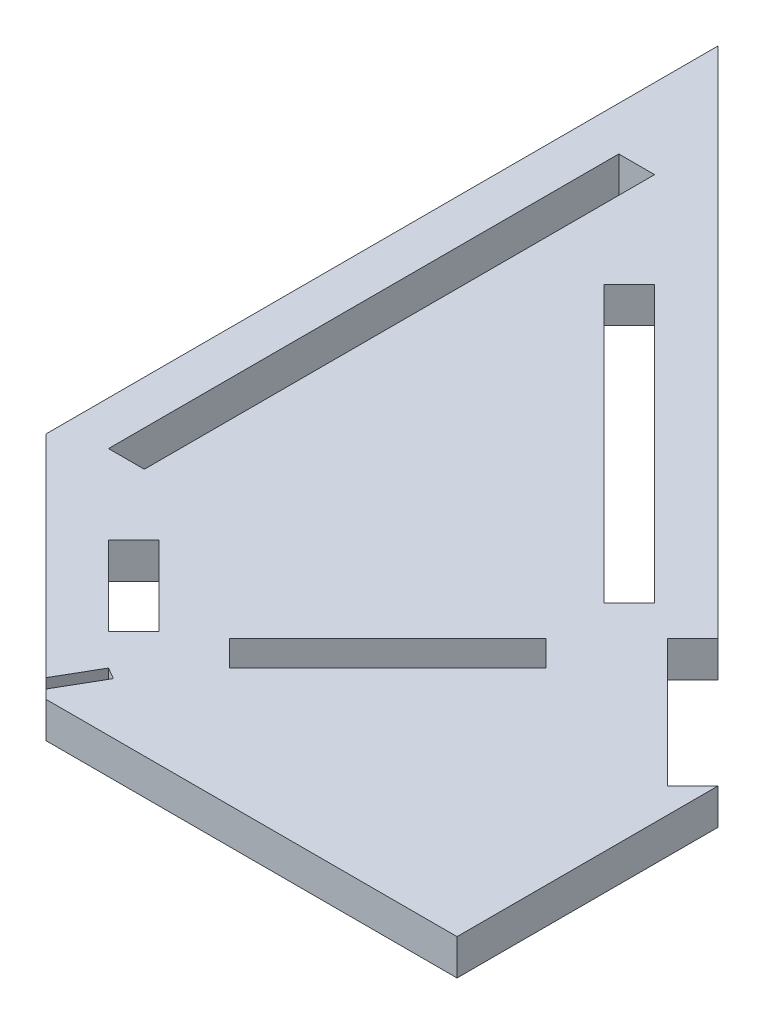
SolidWorks part; units mm, degrees
ref_plane "Front Plane" through (0, 0, 0) normal (0, 0, 1) x (1, 0, 0)
ref_plane "Top Plane" through (0, 0, 0) normal (0, 1, 0) x (1, 0, 0)
ref_plane "Right Plane" through (0, 0, 0) normal (1, 0, 0) x (0, 0, -1)
sketch "Sketch1" plane through (0, 0, 0) normal (0, 1, 0) x (1, 0, 0)
  line L0 (0, 0) -> (0, 58.25)
  line L1 (0, 58.25) -> (-143.0789, 201.3289)
  line L2 (-143.0789, 201.3289) -> (-143.0789, 51.3289)
  line L3 (-143.0789, 51.3289) -> (-95.9462, 4.1962)
  line L4 (-91.75, 0) -> (0, 0)
  line L5 (-93.75, 2) -> (-91.75, 0)
  line L6 (-82.9941, 32.1952) -> (-77.3372, 26.5383) construction
  line L7 (-47.6387, 67.5505) -> (-82.9941, 32.1952) construction
  line L8 (-47.6387, 67.5505) -> (-41.9819, 61.8937) construction
  line L9 (-298.2484, -352.2016) -> (-88.2484, 11.5291)
  line L10 (-88.2484, 11.5291) -> (-90.8465, 13.0291)
  line L11 (-90.8465, 13.0291) -> (-300.8465, -350.7016)
  line L12 (-300.8465, -350.7016) -> (-298.2484, -352.2016)
  line L13 (-93.75, 2) -> (-88.2484, 11.5291)
  line L14 (-88.2484, 11.5291) -> (-90.8465, 13.0291)
  line L15 (-90.8465, 13.0291) -> (-95.9462, 4.1962)
  line L17 (-41.9819, 61.8937) -> (-77.3372, 26.5383) construction
  line L18 (-109.7165, 142.5154) -> (-48.0851, 80.884)
  line L19 (-48.0851, 80.884) -> (-42.4283, 86.5408)
  line L20 (-42.4283, 86.5408) -> (-104.0597, 148.1723)
  line L21 (-104.0597, 148.1723) -> (-109.7165, 142.5154)
  line L22 (-109.7165, 142.5154) -> (-48.0851, 80.884)
  line L23 (-48.0851, 80.884) -> (-42.4283, 86.5408)
  line L24 (-42.4283, 86.5408) -> (-104.0597, 148.1723)
  line L25 (-104.0597, 148.1723) -> (-109.7165, 142.5154)
  line L26 (-115.5952, 37.7778) -> (-97.9175, 20.1001)
  line L27 (-97.9175, 20.1001) -> (-92.2607, 25.757)
  line L28 (-92.2607, 25.757) -> (-109.9384, 43.4346)
  line L29 (-109.9384, 43.4346) -> (-115.5952, 37.7778)
  line L30 (-115.5952, 37.7778) -> (-97.9175, 20.1001)
  line L31 (-97.9175, 20.1001) -> (-92.2607, 25.757)
  line L32 (-92.2607, 25.757) -> (-109.9384, 43.4346)
  line L33 (-109.9384, 43.4346) -> (-115.5952, 37.7778)
  line L34 (-125.2729, 55.4555) -> (-125.2729, 169.3855)
  line L35 (-125.2729, 169.3855) -> (-133.2729, 169.3855)
  line L36 (-133.2729, 169.3855) -> (-133.2729, 55.4555)
  line L37 (-133.2729, 55.4555) -> (-125.2729, 55.4555)
  line L38 (-125.2729, 55.4555) -> (-125.2729, 169.3855)
  line L39 (-125.2729, 169.3855) -> (-133.2729, 169.3855)
  line L40 (-133.2729, 169.3855) -> (-133.2729, 55.4555)
  line L41 (-133.2729, 55.4555) -> (-125.2729, 55.4555)
  line L42 (-82.9941, 32.1952) -> (-77.3372, 26.5383)
  line L43 (-47.6387, 67.5505) -> (-82.9941, 32.1952)
  line L44 (-47.6387, 67.5505) -> (-41.9819, 61.8937)
  line L45 (-41.9819, 61.8937) -> (-77.3372, 26.5383)
  line L55 (-34.1265, 81.0628) -> (-5.6584, 52.5946)
  line L56 (-5.6584, 52.5946) -> (-0.0015, 58.2515)
  line L57 (-0.0015, 58.2515) -> (-28.4696, 86.7196)
  line L58 (-28.4696, 86.7196) -> (-34.1265, 81.0628)
  line L59 (-34.1265, 81.0628) -> (-5.6584, 52.5946)
  line L60 (-5.6584, 52.5946) -> (-0.0015, 58.2515)
  line L61 (-0.0015, 58.2515) -> (-28.4696, 86.7196)
  line L62 (-28.4696, 86.7196) -> (-34.1265, 81.0628)
  dimension "D1" = 135
  dimension "D2" = 150
  dimension "D3" = 72.59
  dimension "D4" = 91.75
  dimension "D5" = 0
  dimension "D6" = 0
  dimension "D7" = 0
  dimension "D8" = 0
  dimension "D9" = 0
extrude "Boss-Extrude1" add sketch "Sketch1" along normal blind 8 contours L62 L1 L2 L3 L15 L14 L13 L5 L4 L0 L59 L41 L40 L39 L38 L33 L32 L31 L30 L25 L24 L23 L22 L44 L45 L42 L43
